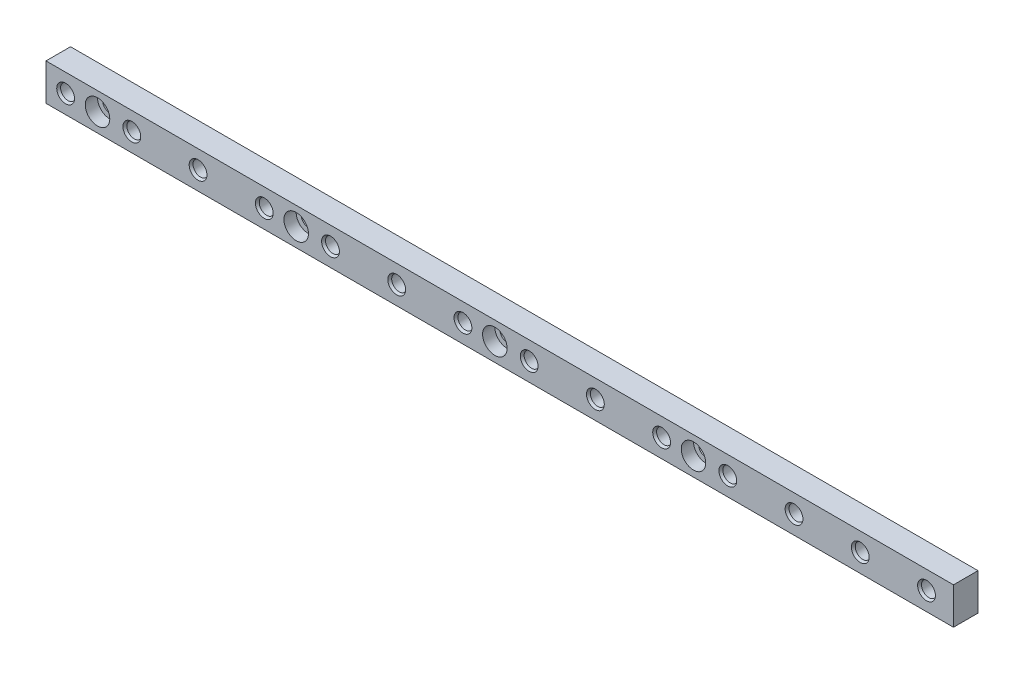
SolidWorks part; units mm, degrees
material "SKD11淬火HRC56-60"
ref_plane "前基準面" through (0, 0, 0) normal (0, 0, 1) x (1, 0, 0)
ref_plane "上基準面" through (0, 0, 0) normal (0, 1, 0) x (1, 0, 0)
ref_plane "右基準面" through (0, 0, 0) normal (1, 0, 0) x (0, 0, -1)
sketch "草图1" plane through (0, 0, 0) normal (0, 0, 1) x (1, 0, 0)
  line L1 (0, 0) -> (370, 0)
  line L2 (0, 0) -> (0, 15)
  line L3 (0, 15) -> (370, 15)
  line L4 (370, 0) -> (370, 15)
  dimension "D1" = 370
  dimension "D2" = 15
extrude "凸台-拉伸1" add sketch "草图1" along normal blind 10
sketch "草图2" plane through (0, 0, 10) normal (0, 0, 1) x (1, 0, 0)
  line L0 (0, 7.5) -> (23.3538, 7.5) construction
  line L1 (0, 15) -> (0, 0) construction
  circle A0 centre (8, 7.5) radius 3.05
  dimension "D1" = 6.1
  dimension "D2" = 8
extrude "切除-拉伸1" cut sketch "草图2" against normal through all
pattern_linear "阵列(线性)1" count 14 spacing 27 along (1, 0, 0) of "切除-拉伸1"
hole_wizard "M5 六角凹头螺钉的柱形沉头孔1" positions "草图4" profile "草图3" counterbore size "M5" standard "ISO" end condition through all
sketch "草图4" plane through (0, 0, 10) normal (0, 0, 1) x (1, 0, 0)
  line L0 (0, 7.5) -> (370, 7.5) construction
  line L1 (0, 15) -> (0, 0) construction
  line L2 (370, 0) -> (370, 15) construction
  point P0 (21, 7.5)
  point P1 (102, 7.5)
  point P3 (183, 7.5)
  point P5 (264, 7.5)
  dimension "D1" = 21
  dimension "D2" = 81
  dimension "D3" = 81
  dimension "D4" = 81
sketch "草图3" plane through (21, 7.5, 10) normal (1, 0, 0) x (0, -1, 0)
  line L0 (0, 0) -> (0, 10)
  line L1 (0, 10) -> (2.9, 10)
  line L3 (2.9, 10) -> (2.9, 5)
  line L4 (2.9, 5) -> (5, 5)
  line L5 (5, 5) -> (5, 0)
  line L7 (5, 0) -> (0, 0)
  line L11 (0, -6.35) -> (0, 107.95) construction
  dimension "通孔孔直径" = 5.8
  dimension "通孔孔深度" = 10
  dimension "柱形沉头孔直径" = 10
  dimension "柱形沉头孔深度" = 5
chamfer "倒角1" distance 1 angle 30 14 edges at (281.05, 7.5, 10) (254.05, 7.5, 10) (227.05, 7.5, 10) (200.05, 7.5, 10) (173.05, 7.5, 10) (146.05, 7.5, 10) (119.05, 7.5, 10) (92.05, 7.5, 10) (65.05, 7.5, 10) (38.05, 7.5, 10) (11.05, 7.5, 10) (308.05, 7.5, 10) (335.05, 7.5, 10) (362.05, 7.5, 10)
